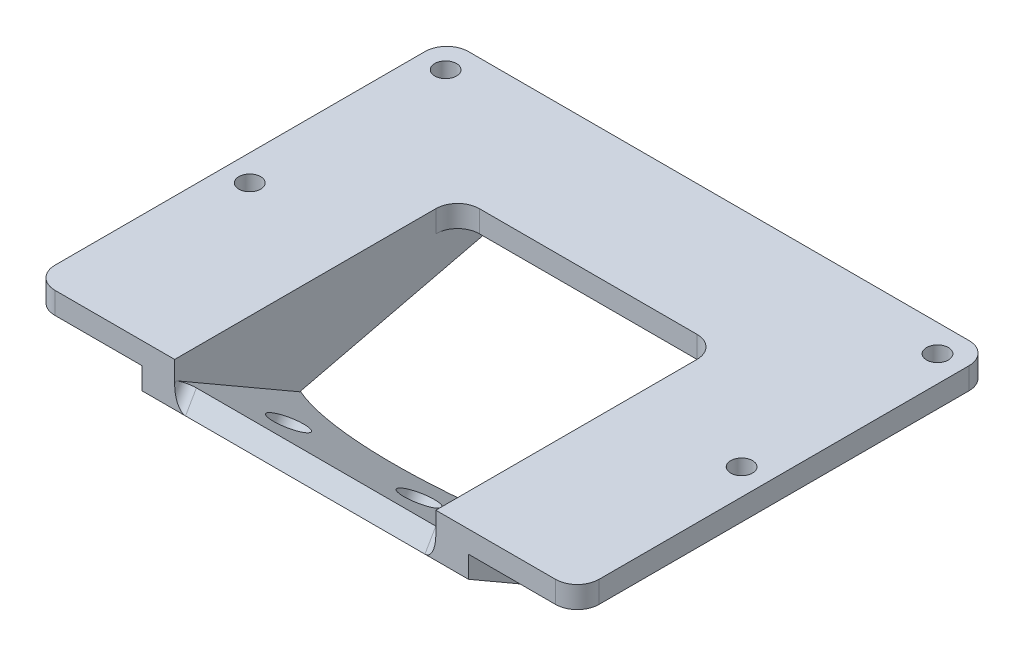
SolidWorks part; units mm, degrees
ref_plane "前视基准面" through (0, 0, 0) normal (0, 0, 1) x (1, 0, 0)
ref_plane "上视基准面" through (0, 0, 0) normal (0, 1, 0) x (1, 0, 0)
ref_plane "右视基准面" through (0, 0, 0) normal (1, 0, 0) x (0, 0, -1)
sketch "草图1" plane through (0, 0, 0) normal (0, 1, 0) x (1, 0, 0)
  line L1 (-22.6, -1.5) -> (22.6, -1.5) construction
  line L2 (-22.6, -1.5) -> (-22.6, 16.5) construction
  line L3 (-22.6, 16.5) -> (22.6, 16.5) construction
  line L4 (22.6, -1.5) -> (22.6, 16.5) construction
  line L5 (-22.6, -1.5) -> (22.6, 16.5) construction
  line L6 (-22.6, 16.5) -> (22.6, -1.5) construction
  line L7 (-25, -19) -> (25, -19)
  line L8 (-25, -19) -> (-25, 19)
  line L9 (-25, 19) -> (25, 19)
  line L10 (25, -19) -> (25, 19)
  line L11 (-25, -19) -> (25, 19) construction
  line L12 (-25, 19) -> (25, -19) construction
  circle A0 centre (-22.6, 16.5) radius 1
  circle A1 centre (-22.6, -1.5) radius 1
  circle A2 centre (22.6, 16.5) radius 1
  circle A3 centre (22.6, -1.5) radius 1
  point P0 (0, 7.5)
  point P10 (0, 0)
  dimension "D3" = 2
  dimension "D1" = 45.2
  dimension "D2" = 18
  dimension "D4" = 50
  dimension "D5" = 38
  dimension "D6" = 2.5
extrude "凸台-拉伸1" add sketch "草图1" along normal blind 2
ref_plane "基准面1" through (12, 0, 0) normal (1, 0, 0) x (0, 0, -1)
sketch "草图3" plane through (12, 0, 0) normal (1, 0, 0) x (0, 0, -1)
  line L2 (-19, -2) -> (-10.3397, -7)
  line L3 (-10.3397, -7) -> (19, 0)
  line L4 (-19, 0) -> (19, 0) construction
  line L5 (-19, 0) -> (19, 0)
  line L6 (-19, 0) -> (-19, -2)
  dimension "D1" = 30
  dimension "D2" = 10
  dimension "D3" = 2
extrude "凸台-拉伸2" add sketch "草图3" along normal blind 3
mirror "镜向1" about plane through (0, 0, 0) normal (1, 0, 0) of "凸台-拉伸2"
sketch "草图5" plane through (0, 2, 0) normal (0, 1, 0) x (1, 0, 0)
  line L0 (-25, -19) -> (25, -19) construction
  line L1 (-12, -19) -> (12, -19)
  line L2 (-12, -19) -> (-12, 7)
  line L3 (-12, 7) -> (12, 7)
  line L4 (12, -19) -> (12, 7)
  line L5 (0, 0) -> (0, 7) construction
  dimension "D1" = 24
  dimension "D2" = 26
extrude "切除-拉伸1" cut sketch "草图5" against normal through all
fillet "圆角1" radius 2 6 edges at (25, 1, 19) (25, 1, -19) (-25, 1, -19) (-25, 1, 19) (-12, 1, -7) (12, 1, -7)
sketch "草图6" plane through (0, -9.7272, 5.616) normal (0, -0.866, 0.5) x (1, 0, 0)
  line L0 (15, 15.4545) -> (15, 5.4545) construction
  line L1 (-15, 15.4545) -> (15, 15.4545)
  line L2 (-15, 15.4545) -> (-15, -0.5455)
  line L3 (-15, -0.5455) -> (15, -0.5455)
  line L4 (15, 15.4545) -> (15, -0.5455)
  line L5 (-15, 15.4545) -> (-15, 5.4545) construction
  line L6 (-15, 15.4545) -> (-12, 15.4545) construction
  dimension "D1" = 16
extrude "凸台-拉伸6" add sketch "草图6" against normal blind 2
sketch "草图7" plane through (0, -9.7272, 5.616) normal (0, -0.866, 0.5) x (1, 0, 0)
  line L0 (-15, 15.4545) -> (-15, -0.5455) construction
  line L1 (15, 15.4545) -> (15, -0.5455) construction
  line L2 (15, -16.4545) -> (15, 16.4545) construction
  line L3 (-15, -0.5455) -> (15, -0.5455) construction
  line L4 (-15, -0.5455) -> (15, -0.5455)
  line L5 (-15, -0.5455) -> (-15, 0.4545)
  line L6 (15, -0.5455) -> (15, 0.4545)
  arc A0 (-15, 0.4545) -> (15, 0.4545) centre (0, -12.7743) cw
  dimension "D1" = 20
  dimension "D2" = 1
extrude "切除-拉伸2" cut sketch "草图7" against normal up to next
fillet "圆角2" radius 1 4 edges at (12, -1.134, 18.5) (-12, -1.134, 18.5) (15, -8.634, 5.5096) (-15, -8.634, 5.5096)
sketch "草图8" plane through (0, -7.9952, 4.616) normal (0, 0.866, -0.5) x (1, 0, 0)
  line L0 (0, 0) -> (0, -11.4389) construction
  line L1 (11, -15.4545) -> (-11, -15.4545) construction
  circle A0 centre (-6, -11.4545) radius 1.6
  circle A1 centre (6, -11.4545) radius 1.6
  dimension "D1" = 3.2
  dimension "D2" = 12
  dimension "D3" = 4
extrude "切除-拉伸3" cut sketch "草图8" against normal up to next
